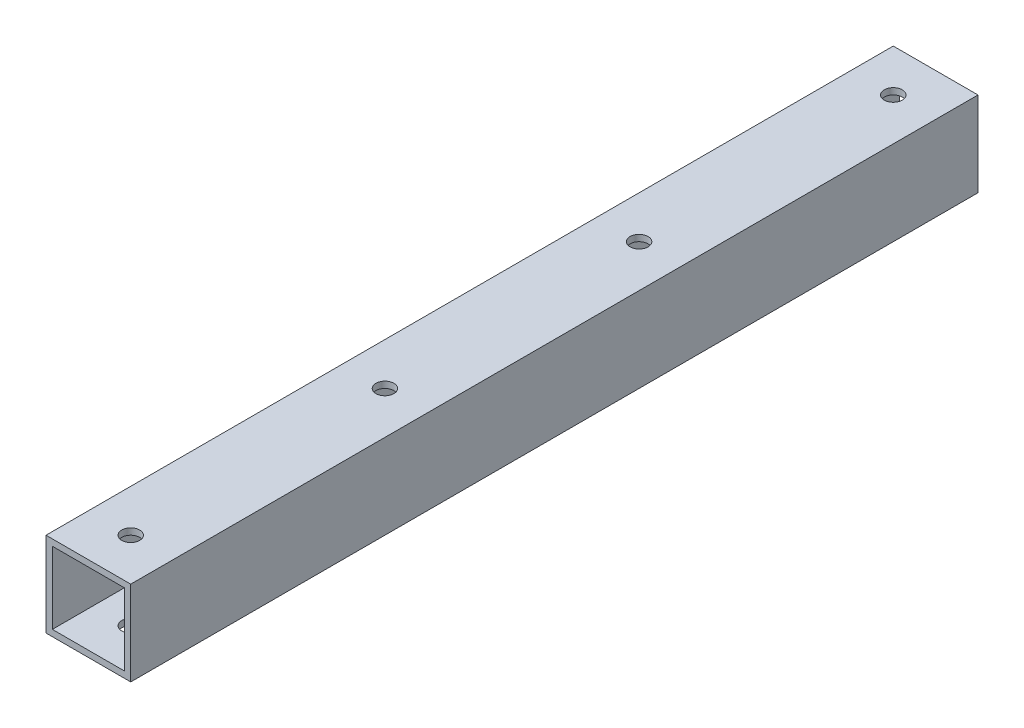
SolidWorks part; units mm, degrees
ref_plane "Front Plane" through (0, 0, 0) normal (0, 0, 1) x (1, 0, 0)
ref_plane "Top Plane" through (0, 0, 0) normal (0, 1, 0) x (1, 0, 0)
ref_plane "Right Plane" through (0, 0, 0) normal (1, 0, 0) x (0, 0, -1)
sketch "Sketch1" plane through (0, 0, 0) normal (0, 0, 1) x (1, 0, 0)
  line L0 (-8.5, -8.5) -> (8.5, -8.5)
  line L1 (-10, -10) -> (10, -10)
  line L2 (-10, -10) -> (-10, 10)
  line L3 (-10, 10) -> (10, 10)
  line L4 (10, -10) -> (10, 10)
  line L5 (-10, -10) -> (10, 10) construction
  line L6 (-10, 10) -> (10, -10) construction
  line L7 (8.5, -8.5) -> (8.5, 8.5)
  line L8 (-8.5, 8.5) -> (8.5, 8.5)
  line L9 (-8.5, -8.5) -> (-8.5, 8.5)
  point P0 (0, 0)
  dimension "D1" = 20
  dimension "D3" = 20
  dimension "D2" = 1.5
extrude "Boss-Extrude1" add sketch "Sketch1" against normal blind 200
sketch "Sketch2" plane through (0, 10, 0) normal (0, 1, 0) x (1, 0, 0)
  line L0 (10, 0) -> (-10, 0) construction
  circle A0 centre (0, 10) radius 2.125
  circle A1 centre (0, 70) radius 2.125
  circle A2 centre (0, 130) radius 2.125
  circle A3 centre (0, 190) radius 2.125
  dimension "D1" = 4.25
  dimension "D2" = 10
  dimension "D3" = 4
extrude "Cut-Extrude1" cut sketch "Sketch2" against normal through all
